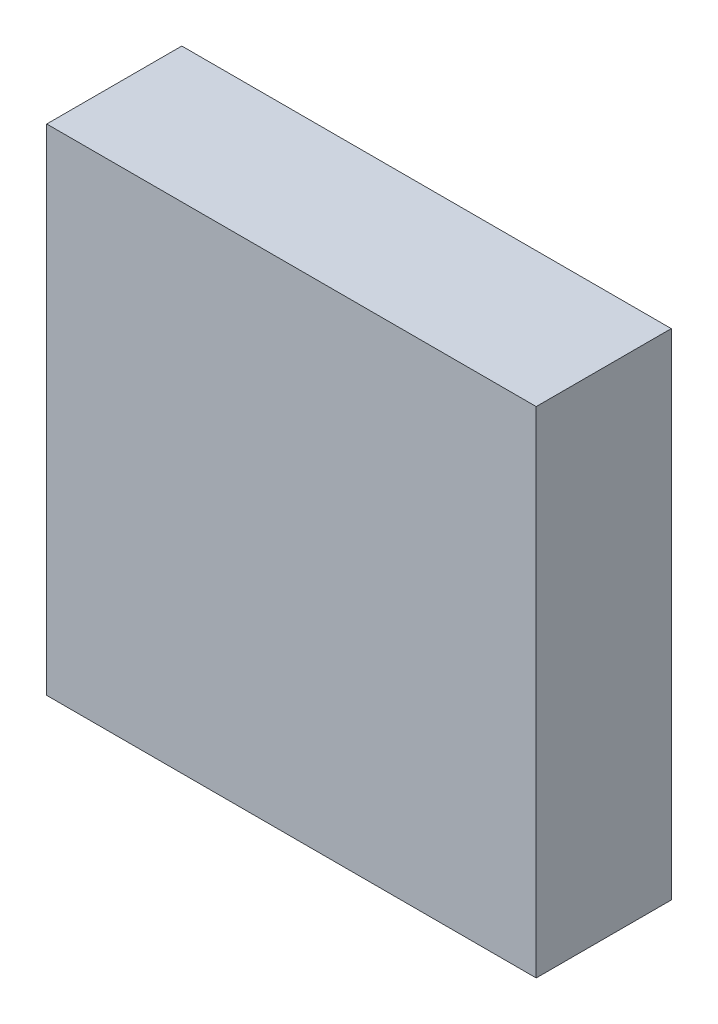
SolidWorks part; units mm, degrees
ref_plane "Front Plane" through (0, 0, 0) normal (0, 0, 1) x (1, 0, 0)
ref_plane "Top Plane" through (0, 0, 0) normal (0, 1, 0) x (1, 0, 0)
ref_plane "Right Plane" through (0, 0, 0) normal (1, 0, 0) x (0, 0, -1)
sketch "Sketch1" plane through (0, 0, 0) normal (0, 0, 1) x (1, 0, 0)
  line L0 (-39.0635, 39.4635) -> (39, 39.4635)
  line L1 (39, 39.4635) -> (39, -39.4635)
  line L2 (39, -39.4635) -> (-39.0635, -39.4635)
  line L3 (-39.0635, -39.4635) -> (-39.0635, 39.4635)
extrude "Component_Outline" add sketch "Sketch1" along normal blind 21.54 separate body
sketch3d "3DSketch1"
  line L0 (0, 0, 0) -> (1, 0, 0)
  line L1 (0, 0, 0) -> (0, 1, 0)
  line L2 (0, 0, 0) -> (0, 0, 1)
  point P0 (0, 0, 0)
